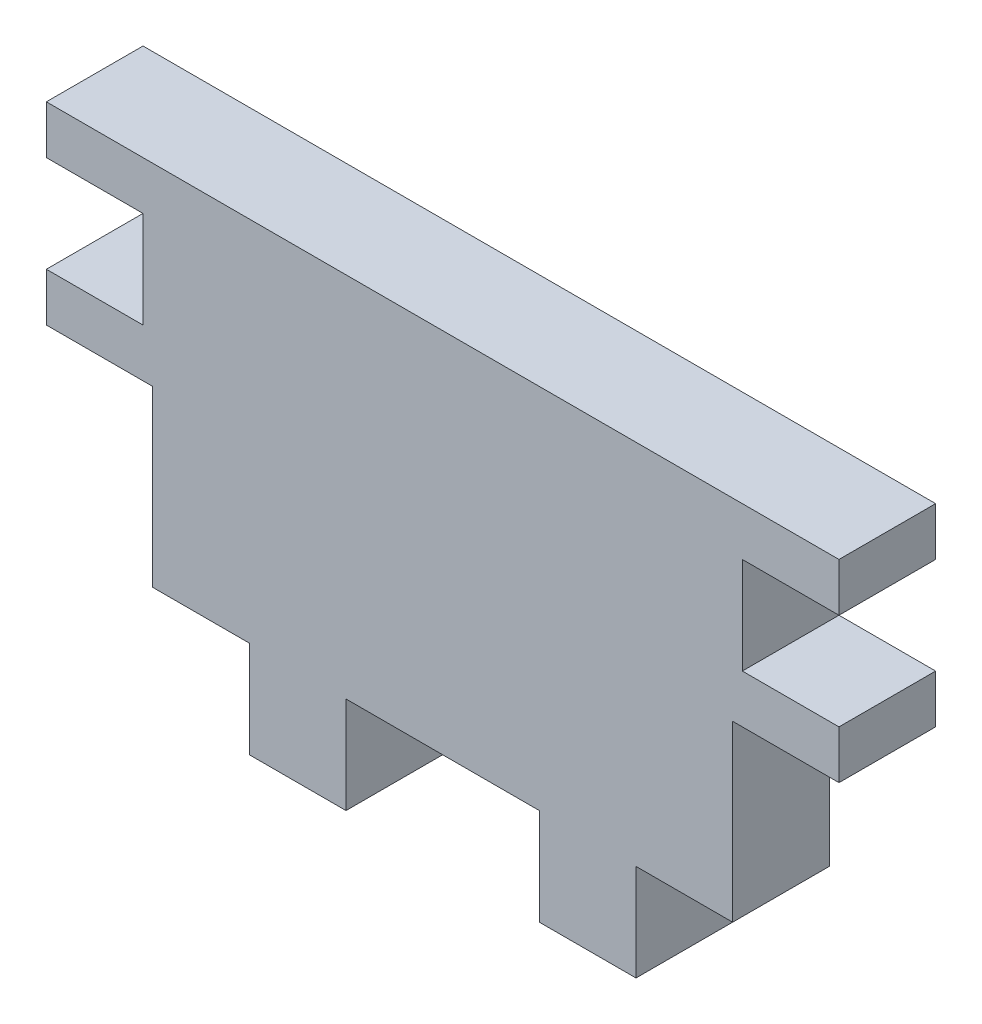
SolidWorks part; units mm, degrees
ref_plane "Plan de face" through (0, 0, 0) normal (0, 0, 1) x (1, 0, 0)
ref_plane "Plan de dessus" through (0, 0, 0) normal (0, 1, 0) x (1, 0, 0)
ref_plane "Plan de droite" through (0, 0, 0) normal (1, 0, 0) x (0, 0, -1)
sketch "Esquisse1" plane through (0, 0, 0) normal (0, 0, 1) x (1, 0, 0)
  line L16 (-36.4015, 16.5191) -> (-36.4015, 7.5191)
  line L19 (-41.9015, 19.0191) -> (-41.9015, 16.5191)
  line L20 (-41.9015, 24.0191) -> (-36.9015, 24.0191)
  line L22 (-41.9015, 19.0191) -> (-36.9015, 19.0191)
  line L23 (-36.9015, 24.0191) -> (-36.9015, 19.0191)
  line L24 (-41.9015, 16.5191) -> (-36.4015, 16.5191)
  line L27 (-41.9015, 24.0191) -> (-41.9015, 26.5191)
  line L29 (-21.4015, 26.5191) -> (-21.4015, 7.5191)
  line L30 (-41.9015, 26.5191) -> (-0.9015, 26.5191)
  line L32 (-31.4015, 7.5191) -> (-31.4015, 2.5191)
  line L33 (-31.4015, 2.5191) -> (-26.4015, 2.5191)
  line L34 (-26.4015, 2.5191) -> (-26.4015, 7.5191)
  line L35 (-26.4015, 7.5191) -> (-16.4015, 7.5191)
  line L36 (-36.4015, 7.5191) -> (-31.4015, 7.5191)
  line L37 (-16.4015, 2.5191) -> (-16.4015, 7.5191)
  line L38 (-11.4015, 2.5191) -> (-16.4015, 2.5191)
  line L39 (-11.4015, 7.5191) -> (-11.4015, 2.5191)
  line L40 (-6.4015, 7.5191) -> (-11.4015, 7.5191)
  line L41 (-6.4015, 16.5191) -> (-6.4015, 7.5191)
  line L42 (-0.9015, 16.5191) -> (-6.4015, 16.5191)
  line L43 (-0.9015, 19.0191) -> (-0.9015, 16.5191)
  line L44 (-0.9015, 19.0191) -> (-5.9015, 19.0191)
  line L45 (-5.9015, 24.0191) -> (-5.9015, 19.0191)
  line L46 (-0.9015, 24.0191) -> (-5.9015, 24.0191)
  line L47 (-0.9015, 24.0191) -> (-0.9015, 26.5191)
  point P5 (0, 0)
  dimension "D1" = 5
  dimension "D2" = 15
  dimension "D3" = 5
  dimension "D4" = 5
  dimension "D5" = 5
  dimension "D6" = 0.5
  dimension "D7" = 2.5
  dimension "D8" = 2.5
  dimension "D9" = 5
  dimension "D10" = 19
  dimension "D11" = 19
extrude "Boss.-Extru.1" add sketch "Esquisse1" along normal blind 5 contours L46 L47 L30 L29 L35 L37 L38 L39 L40 L41 L42 L43 L44 L45 | L16 L36 L32 L33 L34 L35 L29 L30 L27 L20 L23 L22 L19 L24
